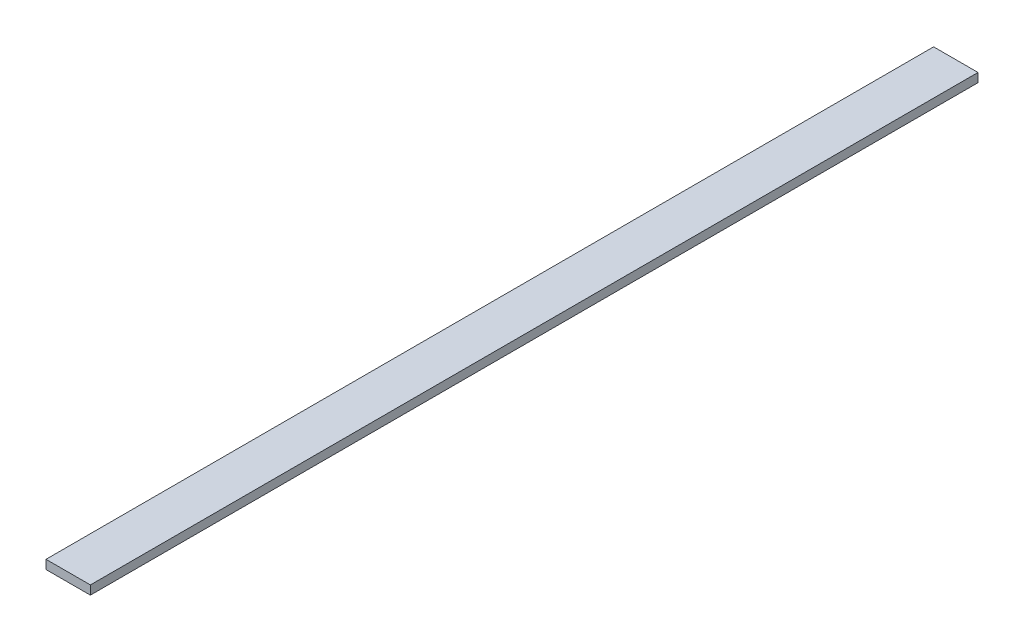
SolidWorks part; units mm, degrees
ref_plane "Front Plane" through (0, 0, 0) normal (0, 0, 1) x (1, 0, 0)
ref_plane "Top Plane" through (0, 0, 0) normal (0, 1, 0) x (1, 0, 0)
ref_plane "Right Plane" through (0, 0, 0) normal (1, 0, 0) x (0, 0, -1)
sketch "Sketch1" plane through (0, 0, 0) normal (0, 1, 0) x (1, 0, 0)
  line L1 (0, 0) -> (10, 0)
  line L2 (0, 0) -> (0, 200)
  line L3 (0, 200) -> (10, 200)
  line L4 (10, 0) -> (10, 200)
  dimension "D1" = 10
  dimension "D2" = 200
extrude "Boss-Extrude1" add sketch "Sketch1" along normal blind 2
